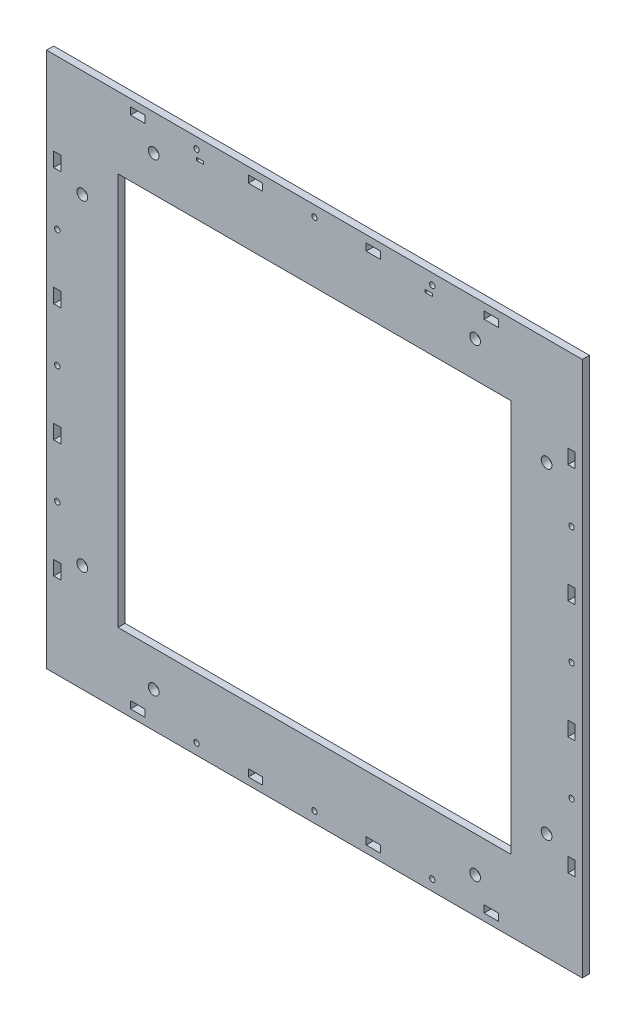
SolidWorks part; units mm, degrees
ref_plane "前视基准面" through (0, 0, 0) normal (0, 0, 1) x (1, 0, 0)
ref_plane "上视基准面" through (0, 0, 0) normal (0, 1, 0) x (1, 0, 0)
ref_plane "右视基准面" through (0, 0, 0) normal (1, 0, 0) x (0, 0, -1)
sketch "草图1" plane through (0, 0, 0) normal (0, 0, 1) x (1, 0, 0)
  line L0 (1.4571, -21.1871) -> (1.4571, -41.1871) construction
  line L1 (63.4571, 98.8129) -> (67.4571, 98.8129)
  line L2 (1.4571, -21.1871) -> (1.4571, 44.8129) construction
  line L3 (67.4571, 98.8129) -> (67.4571, 97.3129)
  line L4 (151.4571, -41.1871) -> (151.4571, 108.8129)
  line L5 (151.4571, 108.8129) -> (-148.5429, 108.8129)
  line L6 (-148.5429, 108.8129) -> (-148.5429, -191.1871)
  line L7 (-148.5429, -191.1871) -> (151.4571, -191.1871)
  line L8 (151.4571, -191.1871) -> (151.4571, -41.1871)
  line L9 (-148.5429, -41.1871) -> (-161.9412, -41.1871) construction
  line L10 (1.4571, -191.1871) -> (1.4571, -181.0361) construction
  line L11 (67.4571, 97.3129) -> (63.4571, 97.3129)
  line L12 (63.4571, 97.3129) -> (63.4571, 98.8129)
  line L13 (-64.5429, 98.8129) -> (-64.5429, 97.3129)
  line L14 (-64.5429, 97.3129) -> (-60.5429, 97.3129)
  line L15 (-60.5429, 97.3129) -> (-60.5429, 98.8129)
  line L16 (-60.5429, 98.8129) -> (-64.5429, 98.8129)
  circle A6 centre (1.4571, -21.1871) radius 241.4173 construction
  circle A9 centre (1.4571, -41.1871) radius 21.5
  circle A10 centre (25.0271, -17.6171) radius 2.1
  circle A11 centre (25.0271, -64.7571) radius 2.1
  circle A12 centre (-22.1129, -64.7571) radius 2.1
  circle A13 centre (-22.1129, -17.6171) radius 2.1
  dimension "D1" = 43
  dimension "D4" = 4.2
  dimension "D2" = 300
  dimension "D3" = 300
  dimension "D5" = 23.57
  dimension "D6" = 23.57
  dimension "D7" = 4
extrude "凸台-拉伸1" add sketch "草图1" along normal blind 4
sketch "草图3" plane through (0, 0, 4) normal (0, 0, 1) x (1, 0, 0)
  line L1 (96.4421, -183.1721) -> (104.4721, -183.1721)
  line L13 (1.4571, -191.1871) -> (1.4571, -185.1871) construction
  line L14 (-148.5429, -191.1871) -> (151.4571, -191.1871) construction
  line L15 (1.4571, -185.1871) -> (34.4571, -185.1871) construction
  line L16 (34.4571, -185.1871) -> (67.4571, -185.1871) construction
  line L17 (30.4421, -183.1721) -> (38.4721, -183.1721)
  line L18 (30.4421, -183.1721) -> (30.4421, -187.2021)
  line L19 (30.4421, -187.2021) -> (38.4721, -187.2021)
  line L20 (38.4721, -183.1721) -> (38.4721, -187.2021)
  line L21 (30.4421, -183.1721) -> (38.4721, -187.2021) construction
  line L22 (30.4421, -187.2021) -> (38.4721, -183.1721) construction
  line L23 (67.4571, -185.1871) -> (100.4571, -185.1871) construction
  line L24 (96.4421, -183.1721) -> (96.4421, -187.2021)
  line L25 (96.4421, -187.2021) -> (104.4721, -187.2021)
  line L26 (96.4421, -187.2021) -> (104.4721, -183.1721) construction
  line L27 (104.4721, -187.2021) -> (104.4721, -183.1721)
  line L28 (-35.5579, -183.1721) -> (-35.5579, -187.2021)
  line L29 (-27.5279, -183.1721) -> (-35.5579, -183.1721)
  line L30 (-27.5279, -183.1721) -> (-27.5279, -187.2021)
  line L31 (-27.5279, -187.2021) -> (-35.5579, -187.2021)
  line L32 (-93.5279, -183.1721) -> (-93.5279, -187.2021)
  line L33 (-101.5579, -187.2021) -> (-101.5579, -183.1721)
  line L34 (-93.5279, -183.1721) -> (-101.5579, -183.1721)
  line L35 (-93.5279, -187.2021) -> (-101.5579, -187.2021)
  line L36 (-140.5279, 53.7979) -> (-140.5279, 61.8279)
  line L37 (-144.5579, 53.7979) -> (-144.5579, 61.8279)
  line L38 (-144.5579, 61.8279) -> (-140.5279, 61.8279)
  line L39 (-140.5279, 53.7979) -> (-144.5579, 53.7979)
  line L40 (-140.5279, -12.2021) -> (-140.5279, -4.1721)
  line L41 (-140.5279, -4.1721) -> (-144.5579, -4.1721)
  line L42 (-144.5579, -12.2021) -> (-144.5579, -4.1721)
  line L43 (-140.5279, -12.2021) -> (-144.5579, -12.2021)
  line L44 (-140.5279, -70.1721) -> (-144.5579, -70.1721)
  line L45 (-140.5279, -70.1721) -> (-140.5279, -78.2021)
  line L46 (-144.5579, -70.1721) -> (-144.5579, -78.2021)
  line L47 (-140.5279, -78.2021) -> (-144.5579, -78.2021)
  line L48 (-140.5279, -136.1721) -> (-140.5279, -144.2021)
  line L49 (-144.5579, -136.1721) -> (-144.5579, -144.2021)
  line L50 (-140.5279, -136.1721) -> (-144.5579, -136.1721)
  line L51 (-144.5579, -144.2021) -> (-140.5279, -144.2021)
  line L52 (96.4421, 100.7979) -> (104.4721, 100.7979)
  line L53 (96.4421, 104.8279) -> (104.4721, 104.8279)
  line L54 (104.4721, 104.8279) -> (104.4721, 100.7979)
  line L55 (96.4421, 100.7979) -> (96.4421, 104.8279)
  line L56 (30.4421, 100.7979) -> (38.4721, 100.7979)
  line L57 (38.4721, 100.7979) -> (38.4721, 104.8279)
  line L58 (30.4421, 104.8279) -> (38.4721, 104.8279)
  line L59 (30.4421, 100.7979) -> (30.4421, 104.8279)
  line L60 (-27.5279, 100.7979) -> (-27.5279, 104.8279)
  line L61 (-27.5279, 100.7979) -> (-35.5579, 100.7979)
  line L62 (-27.5279, 104.8279) -> (-35.5579, 104.8279)
  line L63 (-35.5579, 100.7979) -> (-35.5579, 104.8279)
  line L64 (-93.5279, 100.7979) -> (-101.5579, 100.7979)
  line L65 (-93.5279, 104.8279) -> (-101.5579, 104.8279)
  line L66 (-93.5279, 100.7979) -> (-93.5279, 104.8279)
  line L67 (-101.5579, 104.8279) -> (-101.5579, 100.7979)
  line L68 (143.4421, -136.1721) -> (143.4421, -144.2021)
  line L69 (147.4721, -136.1721) -> (147.4721, -144.2021)
  line L70 (147.4721, -144.2021) -> (143.4421, -144.2021)
  line L71 (143.4421, -136.1721) -> (147.4721, -136.1721)
  line L72 (143.4421, -70.1721) -> (143.4421, -78.2021)
  line L73 (143.4421, -78.2021) -> (147.4721, -78.2021)
  line L74 (147.4721, -70.1721) -> (147.4721, -78.2021)
  line L75 (143.4421, -70.1721) -> (147.4721, -70.1721)
  line L76 (143.4421, -12.2021) -> (147.4721, -12.2021)
  line L77 (143.4421, -12.2021) -> (143.4421, -4.1721)
  line L78 (147.4721, -12.2021) -> (147.4721, -4.1721)
  line L79 (143.4421, -4.1721) -> (147.4721, -4.1721)
  line L80 (143.4421, 53.7979) -> (143.4421, 61.8279)
  line L81 (147.4721, 53.7979) -> (147.4721, 61.8279)
  line L82 (143.4421, 53.7979) -> (147.4721, 53.7979)
  line L83 (147.4721, 61.8279) -> (143.4421, 61.8279)
  line L84 (50.9571, -185.1871) -> (50.9571, -170.1871) construction
  line L85 (17.9571, -185.1871) -> (17.9571, -170.1871) construction
  line L86 (-48.0429, -170.1871) -> (-15.0429, -170.1871) construction
  line L91 (-31.5429, -170.1871) -> (-31.5429, -155.1871) construction
  circle A0 centre (1.4571, -185.1871) radius 1.5
  circle A1 centre (67.4571, -185.1871) radius 1.5
  circle A2 centre (-64.5429, -185.1871) radius 1.5
  circle A3 centre (-142.5429, 24.8129) radius 1.5
  circle A4 centre (-142.5429, -41.1871) radius 1.5
  circle A5 centre (-142.5429, -107.1871) radius 1.5
  circle A6 centre (67.4571, 102.8129) radius 1.5
  circle A7 centre (1.4571, 102.8129) radius 1.5
  circle A8 centre (-64.5429, 102.8129) radius 1.5
  circle A9 centre (145.4571, -107.1871) radius 1.5
  circle A10 centre (145.4571, -41.1871) radius 1.5
  circle A11 centre (145.4571, 24.8129) radius 1.5
  circle A15 centre (17.9571, -170.1871) radius 2 construction
  circle A16 centre (-15.0429, -170.1871) radius 2 construction
  circle A17 centre (50.9571, -170.1871) radius 1.5 construction
  circle A18 centre (-48.0429, -170.1871) radius 1.5 construction
  circle A19 centre (-31.5429, -155.1871) radius 1.5 construction
  circle A20 centre (34.4571, -155.1871) radius 1.5 construction
  circle A22 centre (1.4571, -155.1871) radius 2 construction
  circle A23 centre (1.4571, -41.1871) radius 67.5 construction
  circle A24 centre (1.4571, -108.6871) radius 1.65
  circle A25 centre (-46.2726, -88.9169) radius 1.65
  circle A26 centre (-66.0429, -41.1871) radius 1.65
  circle A27 centre (-46.2726, 6.5426) radius 1.65
  circle A28 centre (1.4571, 26.3129) radius 1.65
  circle A29 centre (49.1869, 6.5426) radius 1.65
  circle A30 centre (68.9571, -41.1871) radius 1.65
  circle A31 centre (49.1869, -88.9169) radius 1.65
  circle A32 centre (1.4571, -125.1871) radius 1.5
  dimension "D1" = 8.03
  dimension "D3" = 4
  dimension "D4" = 8
  dimension "D5" = 30
  dimension "D6" = 3.3
  dimension "D2" = 4.03
extrude "切除-拉伸2" cut sketch "草图3" against normal blind 4
sketch "草图6" plane through (0, 0, 4) normal (0, 0, 1) x (1, 0, 0)
sketch "草图7" plane through (0, 0, 4) normal (0, 0, 1) x (1, 0, 0)
  line L5 (-148.5429, -171.1871) -> (151.4571, -171.1871) construction
  line L6 (-148.5429, 108.8129) -> (-148.5429, -191.1871) construction
  line L7 (151.4571, -191.1871) -> (151.4571, 108.8129) construction
  line L8 (-148.5429, -191.1871) -> (151.4571, -191.1871) construction
  circle A0 centre (-88.5429, -171.1871) radius 3
  circle A1 centre (91.4571, -171.1871) radius 3
  circle A2 centre (-128.5429, 48.8129) radius 3
  circle A3 centre (-128.5429, -131.1871) radius 3
  circle A4 centre (91.4571, 88.8129) radius 3
  circle A5 centre (-88.5429, 88.8129) radius 3
  circle A6 centre (131.4571, -131.1871) radius 3
  circle A7 centre (131.4571, 48.8129) radius 3
  dimension "D2" = 6
  dimension "D4" = 60
  dimension "D1" = 20
  dimension "D3" = 60
  dimension "D5" = 4
extrude "切除-拉伸3" cut sketch "草图7" against normal blind 10
sketch "草图8" plane through (0, 0, 4) normal (0, 0, 1) x (1, 0, 0)
  line L1 (111.4571, -151.1871) -> (-108.5429, -151.1871)
  line L2 (111.4571, -151.1871) -> (111.4571, 68.8129)
  line L3 (111.4571, 68.8129) -> (-108.5429, 68.8129)
  line L4 (-108.5429, -151.1871) -> (-108.5429, 68.8129)
  line L5 (111.4571, -151.1871) -> (-108.5429, 68.8129) construction
  line L6 (111.4571, 68.8129) -> (-108.5429, -151.1871) construction
  point P0 (1.4571, -41.1871)
  dimension "D2" = 220
extrude "切除-拉伸4" cut sketch "草图8" against normal blind 4
